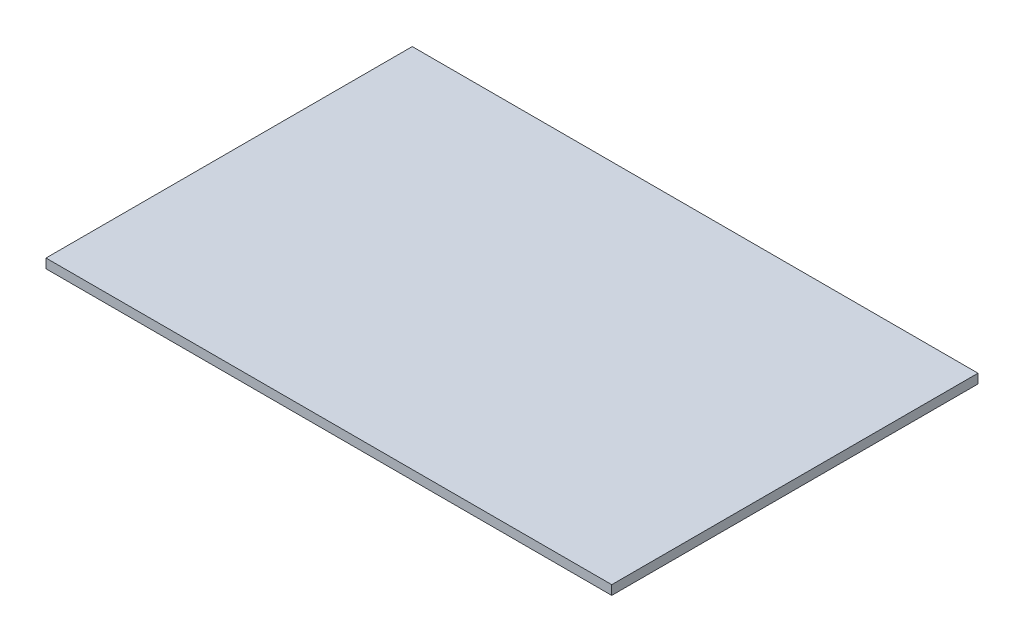
SolidWorks part; units mm, degrees
ref_plane "Front Plane" through (0, 0, 0) normal (0, 0, 1) x (1, 0, 0)
ref_plane "Top Plane" through (0, 0, 0) normal (0, 1, 0) x (1, 0, 0)
ref_plane "Right Plane" through (0, 0, 0) normal (1, 0, 0) x (0, 0, -1)
sketch "Sketch1" plane through (0, 0, 0) normal (0, 1, 0) x (1, 0, 0)
  line L1 (-363, 235) -> (363, 235)
  line L2 (-363, 235) -> (-363, -235)
  line L3 (-363, -235) -> (363, -235)
  line L4 (363, 235) -> (363, -235)
  line L5 (-363, 235) -> (363, -235) construction
  line L6 (-363, -235) -> (363, 235) construction
  point P0 (0, 0)
  dimension "D1" = 726
  dimension "D2" = 470
extrude "Boss-Extrude1" add sketch "Sketch1" along normal blind 12
equation "\"Case_Width\" = 750mm"
equation "\"Case_Depth\" = 470mm"
equation "\"WoodSheet_Thickness\" = 12mm"
equation "\"D1@Boss-Extrude1\"=\"WoodSheet_Thickness\""
equation "\"D1@Sketch1\"=\"Case_Width\"-(\"WoodSheet_Thickness\"*2)"
equation "\"D2@Sketch1\"=\"Case_Depth\""
